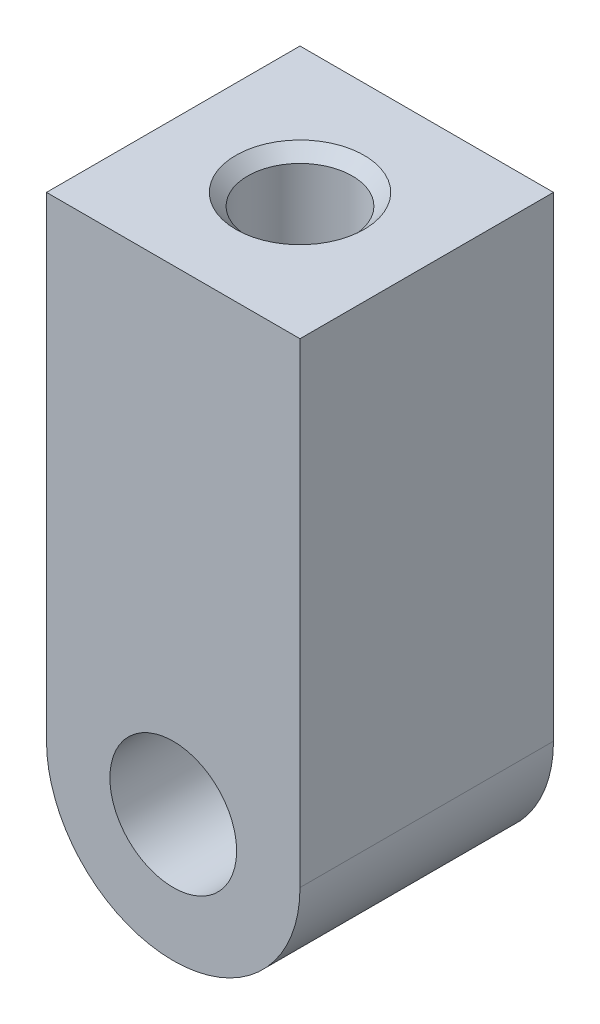
SolidWorks part; units mm, degrees
ref_plane "Спереди" through (0, 0, 0) normal (0, 0, 1) x (1, 0, 0)
ref_plane "Сверху" through (0, 0, 0) normal (0, 1, 0) x (1, 0, 0)
ref_plane "Справа" through (0, 0, 0) normal (1, 0, 0) x (0, 0, -1)
sketch "Эскиз1" plane through (0, 0, 0) normal (0, 0, 1) x (1, 0, 0)
  line L0 (-4, 15) -> (-4, 0)
  line L1 (4, 0) -> (4, 15)
  line L2 (4, 15) -> (-4, 15)
  arc A0 (-4, 0) -> (4, 0) centre (0, 0) ccw
  circle A1 centre (0, 0) radius 2
  dimension "D1" = 4
  dimension "D3" = 15
  dimension "D2" = 8
extrude "Бобышка-Вытянуть1" add sketch "Эскиз1" along normal blind 8
hole_wizard "Отверстие обработанное метчиком M41" positions "Эскиз2" profile "Эскиз4" tap size "M4" standard "ISO"
sketch "Эскиз2" plane through (0, 15, 0) normal (0, 1, 0) x (1, 0, 0)
  line L0 (-4, -4) -> (4, -4) construction
  line L1 (-4, -8) -> (-4, 0) construction
  line L2 (4, -8) -> (4, 0) construction
  point P0 (0, -4)
sketch "Эскиз4" plane through (0, 15, 4) normal (1, 0, 0) x (0, 0, 1)
  line L0 (0, 0) -> (0, 15.9904)
  line L1 (0, 15.9904) -> (1.65, 14.999)
  line L2 (1.65, 14.999) -> (1.65, 0.375)
  line L3 (1.65, 0.375) -> (2.025, 0)
  line L5 (2.025, 0) -> (0, 0)
  line L6 (-1.65, 0.375) -> (-2.025, 0) construction
  line L10 (0, 15.9904) -> (-1.65, 14.999) construction
  line L11 (0, -6.35) -> (0, 107.95) construction
  dimension "Диаметр сверла" = 3.3
  dimension "Глубина сверла" = 14.999
  dimension "Диаметр передней зенковки" = 4.05
  dimension "Угол передней зенковки" = 90
  dimension "Угол заточки сверла" = 118
cosmetic thread "Отверстие резьбы1"
equation "\"D1@Бобышка-Вытянуть1\"=\"D2@Эскиз1\""
